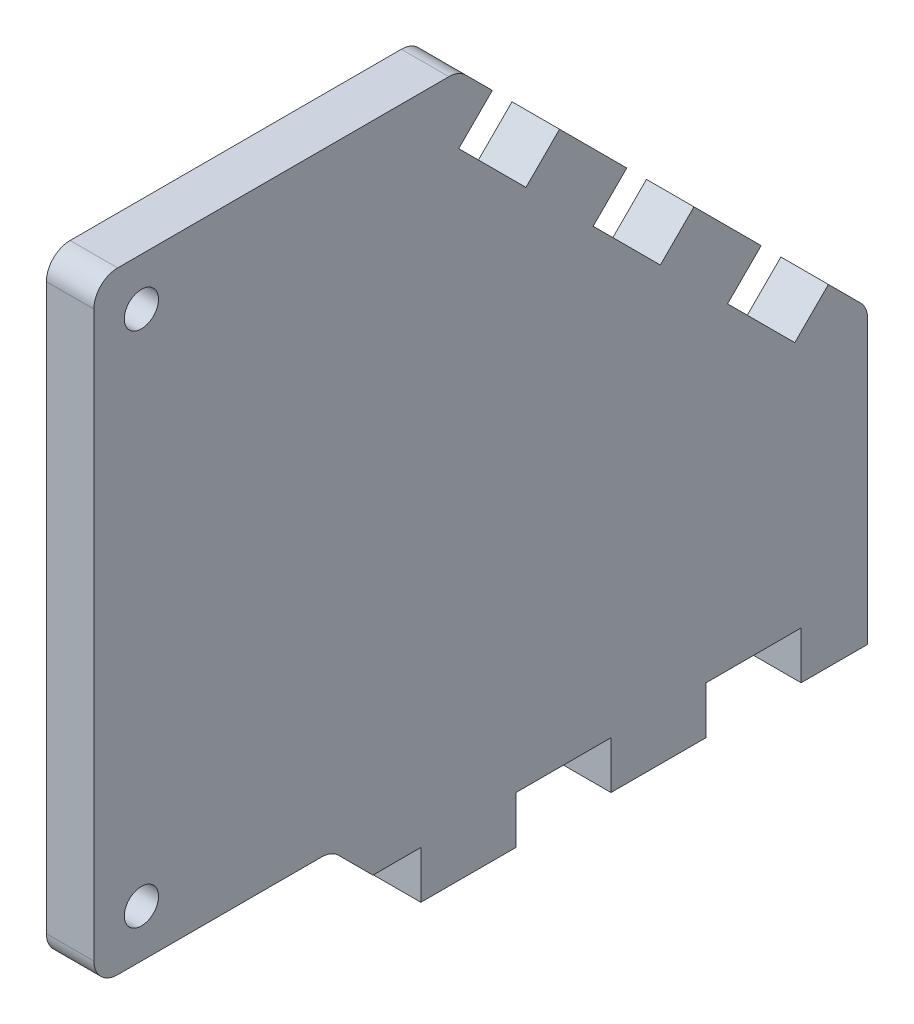
SolidWorks part; units mm, degrees
material "Custom Plastic"
ref_plane "Front Plane" through (0, 0, 0) normal (0, 0, 1) x (1, 0, 0)
ref_plane "Top Plane" through (0, 0, 0) normal (0, 1, 0) x (1, 0, 0)
ref_plane "Right Plane" through (0, 0, 0) normal (1, 0, 0) x (0, 0, -1)
sketch "Sketch2" plane through (0, 0, 0) normal (1, 0, 0) x (0, 0, -1)
  line L0 (0, 0) -> (0, 26.162) construction
  line L1 (0, 26.162) -> (0, 95.25) construction
  line L2 (-55.118, 95.25) -> (0, 95.25) construction
  line L3 (-61.468, 95.25) -> (-61.468, 26.162) construction
  line L4 (-61.468, 26.162) -> (0, 26.162) construction
  line L5 (-45.72, 0) -> (45.72, 0)
  line L6 (-67.818, 101.6) -> (-67.818, 19.812)
  line L7 (45.72, 7.9375) -> (-29.718, 7.9375)
  line L8 (45.72, 0) -> (52.07, 0)
  line L9 (-67.818, 19.812) -> (-45.72, 0)
  line L10 (-55.118, 101.6) -> (-19.0732, 101.6)
  line L11 (-61.468, 95.25) -> (-61.468, 101.6) construction
  line L12 (-61.468, 95.25) -> (-67.818, 95.25) construction
  line L13 (-61.468, 26.162) -> (-67.818, 26.162) construction
  line L14 (-61.468, 26.162) -> (-61.468, 19.812) construction
  line L15 (-55.118, 101.6) -> (-67.818, 101.6)
  line L16 (-61.468, 95.25) -> (-55.118, 95.25) construction
  line L17 (-36.068, 19.812) -> (-29.718, 13.462)
  line L18 (-55.118, 95.25) -> (-55.118, 101.6) construction
  line L19 (-67.818, 19.812) -> (-36.068, 19.812)
  line L20 (-29.718, 13.462) -> (-29.718, 7.9375)
  line L21 (52.07, 0) -> (52.07, 7.9375)
  line L22 (52.07, 7.9375) -> (45.72, 7.9375)
  line L23 (-29.718, 7.9375) -> (-24.1935, 7.9375)
  line L24 (-19.0732, 101.6) -> (52.07, 30.4568)
  line L25 (52.07, 30.4568) -> (52.07, 7.9375)
  circle A0 centre (-61.468, 95.25) radius 2.286
  circle A1 centre (-61.468, 26.162) radius 2.286
  point P0 (0, 0)
  point P1 (-61.468, 95.25)
  point P3 (-61.468, 26.162)
  dimension "D4" = 4.572
  dimension "D7" = 6.35
  dimension "D2" = 26.162
  dimension "D3" = 61.468
  dimension "D5" = 7.9375
  dimension "D6" = 91.44
  dimension "D8" = 6.35
  dimension "D9" = 31.75
  dimension "D10" = 45
  dimension "D11" = 95.25
  dimension "D12" = 6.35
  dimension "D13" = 69.85
extrude "Main" add sketch "Sketch2" along normal blind 6.35
sketch "Sketch5" plane through (6.35, 0, 0) normal (1, 0, 0) x (0, 0, -1)
  line L0 (-36.83, 7.9375) -> (-36.83, 14.2875)
  line L1 (52.07, 7.9375) -> (-29.718, 7.9375) construction
  line L2 (-36.83, 14.2875) -> (-24.13, 14.2875)
  line L3 (-24.13, 14.2875) -> (-24.13, 7.9375)
  line L4 (-24.13, 7.9375) -> (-11.43, 7.9375) construction
  line L5 (-11.43, 7.9375) -> (-11.43, 14.2875)
  line L6 (-11.43, 14.2875) -> (1.27, 14.2875)
  line L7 (1.27, 14.2875) -> (1.27, 7.9375)
  line L8 (1.27, 7.9375) -> (13.97, 7.9375) construction
  line L9 (13.97, 7.9375) -> (13.97, 14.2875)
  line L10 (13.97, 14.2875) -> (26.67, 14.2875)
  line L11 (26.67, 14.2875) -> (26.67, 7.9375)
  line L12 (-19.0732, 101.6) -> (52.07, 30.4568) construction
  line L13 (-36.83, 7.9375) -> (-24.13, 7.9375)
  line L14 (-11.43, 7.9375) -> (1.27, 7.9375)
  line L15 (13.97, 7.9375) -> (26.67, 7.9375)
  line L16 (12.3577, 70.1691) -> (21.338, 61.1888) construction
  line L21 (16.8478, 56.6987) -> (21.338, 61.1888)
  line L22 (25.8281, 47.7185) -> (16.8478, 56.6987)
  line L23 (30.3182, 52.2086) -> (25.8281, 47.7185)
  line L24 (21.338, 61.1888) -> (30.3182, 52.2086)
  line L25 (-1.1127, 74.6592) -> (3.3775, 79.1494)
  line L26 (7.8676, 65.679) -> (-1.1127, 74.6592)
  line L27 (12.3577, 70.1691) -> (7.8676, 65.679)
  line L28 (3.3775, 79.1494) -> (12.3577, 70.1691)
  line L29 (-19.0732, 92.6197) -> (-14.5831, 97.1099)
  line L30 (-10.0929, 83.6395) -> (-19.0732, 92.6197)
  line L31 (-5.6028, 88.1296) -> (-10.0929, 83.6395)
  line L32 (-14.5831, 97.1099) -> (-5.6028, 88.1296)
  line L33 (-5.6028, 88.1296) -> (3.3775, 79.1494) construction
  line L35 (39.37, 7.9375) -> (39.37, 43.1568)
  line L36 (52.07, 7.9375) -> (-29.718, 7.9375) construction
  line L37 (39.37, 43.1568) -> (52.07, 43.1568)
  line L38 (52.07, 43.1568) -> (52.07, 7.9375)
  line L39 (52.07, 7.9375) -> (39.37, 7.9375)
  line L40 (26.67, 7.9375) -> (39.37, 7.9375) construction
  line L41 (52.07, 30.4568) -> (52.07, 7.9375) construction
  dimension "D5" = 6.35
  dimension "D1" = 6.35
  dimension "D2" = 12.7
extrude "Acrylic Joint" cut sketch "Sketch5" against normal through all
sketch "Sketch6" plane through (6.35, 0, 0) normal (1, 0, 0) x (0, 0, -1)
  line L0 (35.56, 7.9375) -> (35.56, 46.9668)
  line L1 (39.37, 7.9375) -> (26.67, 7.9375) construction
  line L2 (35.56, 46.9668) -> (39.37, 46.9668)
  line L3 (39.37, 43.1568) -> (39.37, 7.9375) construction
  line L4 (39.37, 46.9668) -> (39.37, 7.9375)
  line L5 (39.37, 7.9375) -> (35.56, 7.9375)
  line L6 (30.3182, 52.2086) -> (39.37, 43.1568) construction
  dimension "D2" = 3.81
extrude "Cut-Extrude1" cut sketch "Sketch6" against normal through all
fillet "Fillet4" radius 3.175 5 edges at (3.175, 101.6, 67.818) (3.175, 19.812, 67.818) (3.175, 19.812, 36.068) (3.175, 101.6, 19.0732) (3.175, 46.9668, -35.56)
